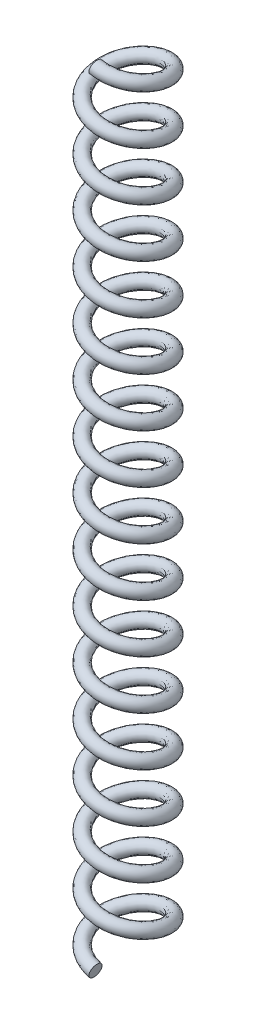
SolidWorks part; units mm, degrees
ref_plane "Front Plane" through (0, 0, 0) normal (0, 0, 1) x (1, 0, 0)
ref_plane "Top Plane" through (0, 0, 0) normal (0, 1, 0) x (1, 0, 0)
ref_plane "Right Plane" through (0, 0, 0) normal (1, 0, 0) x (0, 0, -1)
other "Configuration Table"
sketch "Sketch1" plane through (0, 0, 0) normal (0, 1, 0) x (1, 0, 0)
  circle A0 centre (0, 0) radius 2.5
curve "Coil_Helix" pitch 3.7642 height 60.2279 turns 16
sweep "Coil_Wire" add path "Coil_Helix" circular profile diameter 1 parameters "D3"=1
